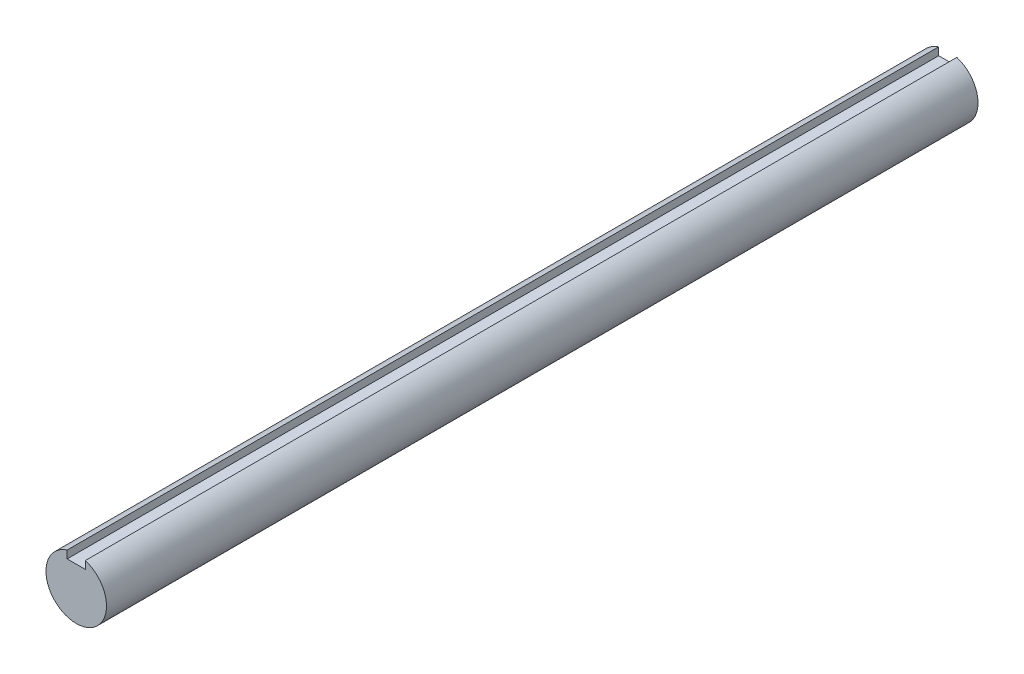
SolidWorks part; units mm, degrees
ref_plane "Front Plane" through (0, 0, 0) normal (0, 0, 1) x (1, 0, 0)
ref_plane "Top Plane" through (0, 0, 0) normal (0, 1, 0) x (1, 0, 0)
ref_plane "Right Plane" through (0, 0, 0) normal (1, 0, 0) x (0, 0, -1)
sketch "Sketch1" plane through (0, 0, 0) normal (1, 0, 0) x (0, 0, -1)
  line L0 (0, 0) -> (0, 3.9687) construction
  line L1 (-57.15, 3.9687) -> (57.15, 3.9688)
  line L2 (-57.15, 3.9687) -> (-57.15, -3.9688)
  line L3 (-57.15, -3.9688) -> (57.15, -3.9687)
  line L4 (57.15, 3.9688) -> (57.15, -3.9687)
  line L5 (-57.15, 3.9687) -> (57.15, -3.9687) construction
  line L6 (-57.15, -3.9688) -> (57.15, 3.9688) construction
  line L7 (0, 0) -> (0, -3.9688) construction
  line L8 (57.15, 3.9687) -> (-57.15, 3.9687) construction
  point P0 (0, 0)
  point P8 (-48.0219, 3.9687)
  point P10 (48.0219, 3.9687)
  point P11 (-44.9792, -3.9687)
  point P12 (46.6098, -3.9687)
  point P15 (0, 3.9687)
  dimension "Diameter" = 7.9375
  dimension "Length" = 114.3
  dimension "D1" = 9.1281
  dimension "D2" = 9.1281
  dimension "D3" = 12.1708
  dimension "D4" = 10.5402
  dimension "Key Length" = 114.3
sketch "Sketch2" plane through (0, 0, 0) normal (0, 0, 1) x (1, 0, 0)
  line L0 (0, 0) -> (0, 3.9687) construction
  line L2 (1.1938, 2.7749) -> (-1.1938, 2.7749)
  line L3 (1.1938, 2.7749) -> (1.1938, 3.9687)
  line L4 (1.1938, 3.9687) -> (-1.1938, 3.9687)
  line L5 (-1.1938, 2.7749) -> (-1.1938, 3.9687)
  line L6 (1.1938, 2.7749) -> (-1.1938, 3.9687) construction
  line L7 (1.1938, 3.9687) -> (-1.1938, 2.7749) construction
  circle A0 centre (0, 0) radius 3.9687
  point P3 (0, 3.3718)
  dimension "Keyway Width" = 2.3876
  dimension "Keyway Depth" = 1.1938
sketch "Sketch3" plane through (0, 0, 0) normal (0, 0, 1) x (1, 0, 0)
  line L1 (-1.1938, 2.7749) -> (-1.1938, 3.9687) construction
  line L2 (1.1938, 2.7749) -> (-1.1938, 2.7749) construction
  line L3 (1.1938, 2.7749) -> (1.1938, 3.9687) construction
  line L5 (-1.1938, 2.7749) -> (-1.1938, 3.7849)
  line L6 (1.1938, 2.7749) -> (-1.1938, 2.7749)
  line L7 (1.1938, 2.7749) -> (1.1938, 3.7849)
  arc A1 (-1.1938, 3.7849) -> (1.1938, 3.7849) centre (0, 0) ccw
  circle A2 centre (0, 0) radius 3.9687 construction
extrude "Boss-Extrude1" add sketch "Sketch3" along normal up to vertex (57.15 mm away) and the other way up to vertex (57.15 mm away) up to point (0, 3.9687, 57.15) other way up to point (0, 3.9688, -57.15)
chamfer "Chamfer1" [suppressed] distance 0.0794 angle 45
equation "\"D2@Sketch1\"=1.15*\"Diameter@Sketch1\""
equation "\"D1@Sketch1\"=\"D2@Sketch1\""
equation "\"D3@Sketch1\"=\"D2@Sketch1\"*4/3"
equation "\"D4@Sketch1\"=\"D2@Sketch1\"/(tan(.5236*180/pi)*2)*4/3"
equation "\"D1@Chamfer1\"=\"Diameter@Sketch1\"*.01"
equation "\"Key Length@Sketch1\"=\"Length@Sketch1\""
